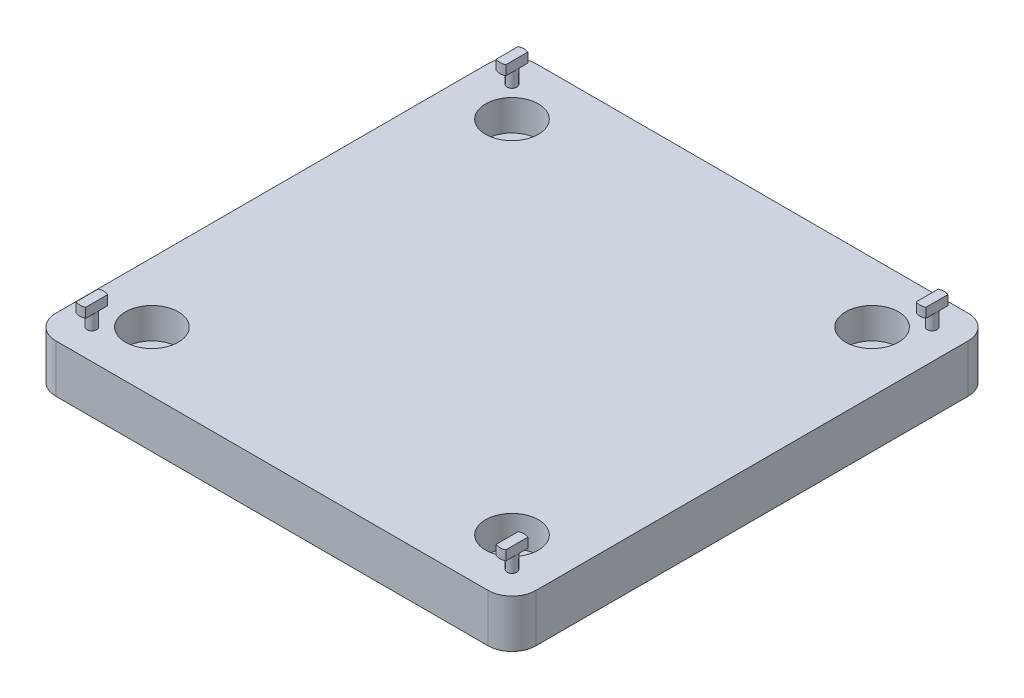
SolidWorks part; units mm, degrees
ref_plane "Front Plane" through (0, 0, 0) normal (0, 0, 1) x (1, 0, 0)
ref_plane "Top Plane" through (0, 0, 0) normal (0, 1, 0) x (1, 0, 0)
ref_plane "Right Plane" through (0, 0, 0) normal (1, 0, 0) x (0, 0, -1)
sketch "Sketch1" plane through (0, 0, 0) normal (0, 1, 0) x (1, 0, 0)
  line L0 (-37.5, 37.5) -> (-37.5, -37.5) construction
  line L1 (-50, 50) -> (50, 50)
  line L2 (-50, 50) -> (-50, -50)
  line L3 (-50, -50) -> (50, -50)
  line L4 (50, 50) -> (50, -50)
  line L5 (-50, 50) -> (50, -50) construction
  line L6 (-50, -50) -> (50, 50) construction
  line L7 (37.5, 37.5) -> (37.5, -37.5) construction
  line L8 (37.5, -37.5) -> (-37.5, -37.5) construction
  line L9 (-37.5, 37.5) -> (37.5, 37.5) construction
  point P0 (0, 0)
  point P6 (-37.5, -37.5)
  point P7 (37.5, 37.5)
  point P8 (-37.5, 37.5)
  point P9 (37.5, -37.5)
  dimension "D1" = 75
  dimension "D2" = 12.5
extrude "Boss-Extrude1" add sketch "Sketch1" along normal blind 10
hole_wizard "CBORE for M6 Hex Socket Head Cap Screw1" positions "Sketch2" profile "Sketch3" counterbore size "M6" standard "ISO"
sketch "Sketch2" plane through (0, 10, 0) normal (0, 1, 0) x (1, 0, 0)
  point P0 (-37.5, -37.5)
  point P2 (37.5, -37.5)
  point P4 (37.5, 37.5)
  point P6 (-37.5, 37.5)
sketch "Sketch3" plane through (-37.5, 10, 37.5) normal (1, 0, 0) x (0, 0, 1)
  line L0 (0, 0) -> (0, 20.05)
  line L1 (0, 20.05) -> (3.5, 17.947)
  line L2 (3.5, 17.947) -> (3.5, 6.4)
  line L3 (3.5, 6.4) -> (5.5, 6.4)
  line L4 (5.5, 6.4) -> (5.5, 0)
  line L5 (5.5, 0) -> (0, 0)
  line L10 (0, 20.05) -> (-3.5, 17.947) construction
  line L11 (0, -6.35) -> (0, 107.95) construction
  dimension "Hole Dia." = 7
  dimension "Hole Depth" = 20.05
  dimension "C'Bore Dia." = 11
  dimension "C'Bore Depth" = 6.4
  dimension "Drill Angle" = 118
fillet "Fillet1" radius 5 4 edges at (50, 5, 50) (-50, 5, 50) (-50, 5, -50) (50, 5, -50)
sketch "Sketch4" plane through (0, 10, 0) normal (0, 1, 0) x (1, 0, 0)
  line L0 (-43.75, 43.75) -> (-43.75, -43.75) construction
  line L1 (-43.75, -43.75) -> (43.75, -43.75) construction
  line L2 (43.75, 43.75) -> (43.75, -43.75) construction
  line L3 (-43.75, 43.75) -> (43.75, 43.75) construction
  circle A0 centre (-43.75, 43.75) radius 1
  circle A1 centre (43.75, 43.75) radius 1
  circle A2 centre (-43.75, -43.75) radius 1
  circle A3 centre (43.75, -43.75) radius 1
  point P0 (-43.75, 43.75)
  point P1 (43.75, 43.75)
  point P2 (43.75, -43.75)
  point P3 (-43.75, -43.75)
  point P6 (0, -43.75)
  point P10 (43.75, 0)
  dimension "D3" = 2
  dimension "D4" = 2
  dimension "D1" = 87.5
  dimension "D2" = 87.5
extrude "Boss-Extrude2" add sketch "Sketch4" along normal blind 3.2
sketch "Sketch5" plane through (0, 13.2, 0) normal (0, 1, 0) x (1, 0, 0)
  circle A0 centre (-43.75, 43.75) radius 2.5
  circle A1 centre (43.75, 43.75) radius 2.5
  circle A2 centre (43.75, -43.75) radius 2.5
  circle A3 centre (-43.75, -43.75) radius 2.5
  dimension "D1" = 5
extrude "Boss-Extrude3" add sketch "Sketch5" along normal blind 2
sketch "Sketch6" plane through (0, 15.2, 0) normal (0, 1, 0) x (1, 0, 0)
  line L0 (-44.75, 41.4587) -> (-44.75, 46.0413)
  line L1 (-42.75, 46.0413) -> (-42.75, 41.4587)
  circle A0 centre (-43.75, 43.75) radius 2.5 construction
  circle A2 centre (-43.75, 43.75) radius 2.5
  circle A3 centre (-43.75, 43.75) radius 2.5
  circle M4 centre (-43.75, 43.75) radius 2.5
  dimension "D2" = 2
  dimension "D1" = 0
extrude "Cut-Extrude1" cut sketch "Sketch6" against normal blind 3 contours L0 M4 | L1 M4 | A3
pattern_linear "LPattern1" count 2 spacing 87.5 along (0, 0, 1) count 2 spacing 87.5 along (1, 0, 0) of "Cut-Extrude1"
